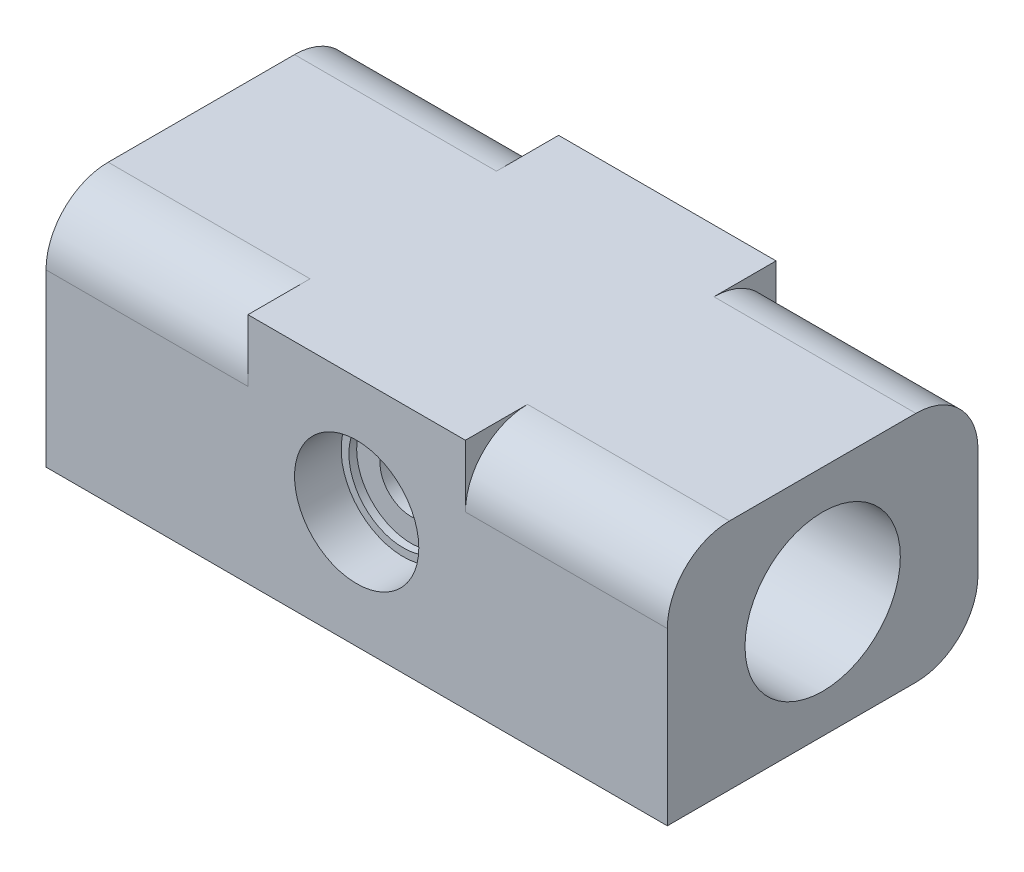
SolidWorks part; units mm, degrees
material "ABS"
ref_plane "前基準面" through (0, 0, 0) normal (0, 0, 1) x (1, 0, 0)
ref_plane "上基準面" through (0, 0, 0) normal (0, 1, 0) x (1, 0, 0)
ref_plane "右基準面" through (0, 0, 0) normal (1, 0, 0) x (0, 0, -1)
sketch "草圖1" plane through (0, 0, 0) normal (1, 0, 0) x (0, 0, -1)
  line L1 (-10, 7.5) -> (10, 7.5)
  line L2 (-10, 7.5) -> (-10, -7.5)
  line L3 (-10, -7.5) -> (10, -7.5)
  line L4 (10, 7.5) -> (10, -7.5)
  line L5 (-10, 7.5) -> (10, -7.5) construction
  line L6 (-10, -7.5) -> (10, 7.5) construction
  circle A0 centre (0, 0) radius 5
  point P0 (0, 0)
  dimension "D1" = 10
  dimension "D2" = 20
  dimension "D3" = 15
extrude "填料-伸長1" add sketch "草圖1" along normal blind 40
sketch "草圖2" plane through (0, 0, 10) normal (0, 0, 1) x (1, 0, 0)
  line L0 (0, 0) -> (40, 0) construction
  line L1 (0, 7.5) -> (0, -7.5) construction
  line L2 (40, 7.5) -> (40, -7.5) construction
  circle A1 centre (20, 0) radius 4
  dimension "D2" = 8
extrude "除料-伸長1" cut sketch "草圖2" against normal blind 3
mirror "鏡射1" about plane through (0, 0, 0) normal (0, 0, 1) of "除料-伸長1"
sketch "草圖3" plane through (0, 0, 7) normal (0, 0, 1) x (1, 0, 0)
  circle A0 centre (20, 0) radius 2
  dimension "D1" = 4
extrude "除料-伸長2" cut sketch "草圖3" against normal through all
sketch "草圖4" plane through (0, 0, 0) normal (-1, 0, 0) x (0, 0, 1)
  line L1 (-6, 7.5) -> (6, 7.5)
  line L2 (-10, 3.5) -> (-10, -3.5)
  line L3 (-6, -7.5) -> (10, -7.5)
  line L4 (10, 3.5) -> (10, -7.5)
  line L5 (-10, 7.5) -> (10, -7.5) construction
  line L6 (-10, -7.5) -> (10, 7.5) construction
  line L7 (-13.2969, 9.2023) -> (13.2969, 9.2023)
  line L8 (-13.2969, 9.2023) -> (-13.2969, -9.2023)
  line L9 (-13.2969, -9.2023) -> (13.2969, -9.2023)
  line L10 (13.2969, 9.2023) -> (13.2969, -9.2023)
  line L11 (-13.2969, 9.2023) -> (13.2969, -9.2023) construction
  line L12 (-13.2969, -9.2023) -> (13.2969, 9.2023) construction
  arc A0 (-6, 7.5) -> (-10, 3.5) centre (-6, 3.5) ccw
  arc A1 (-10, -3.5) -> (-6, -7.5) centre (-6, -3.5) ccw
  arc A3 (6, 7.5) -> (10, 3.5) centre (6, 3.5) cw
  point P0 (0, 0)
  point P7 (0, 0)
  dimension "D1" = 4
extrude "除料-伸長3" cut sketch "草圖4" against normal blind 13
ref_plane "平面1" through (20, 0, 0) normal (1, 0, 0) x (0, 0, -1)
mirror "鏡射2" about plane through (20, 0, 0) normal (1, 0, 0) of "除料-伸長3"
sketch "草圖5" plane through (0, 0, -7) normal (0, 0, -1) x (-1, 0, 0)
  circle A0 centre (-20, 0) radius 3.5
  dimension "D1" = 7
extrude "除料-伸長4" cut sketch "草圖5" against normal blind 0.5
mirror "鏡射3" about plane through (0, 0, 0) normal (0, 0, 1) of "除料-伸長4"
sketch "草圖6" plane through (0, 0, -10) normal (0, 0, 1) x (1, 0, 0)
  line L0 (17.25, -4.7631) -> (15.6699, -7.5) construction
  line L2 (15.6699, -7.5) -> (24.3301, -7.5)
  line L4 (24.3301, -7.5) -> (22.75, -4.7631) construction
  line L5 (20, -8.25) -> (20, 8.25) construction
  line L6 (22.75, -4.7631) -> (27.7296, -1.8881)
  line L7 (12.2704, -1.8881) -> (9.5818, -2.5449)
  line L8 (33.2791, -7.5) -> (24.3301, -7.5)
  line L9 (17.25, -4.7631) -> (12.2704, -1.8881)
  line L10 (9.5818, -2.5449) -> (6.7209, -7.5)
  line L12 (6.7209, -7.5) -> (15.6699, -7.5)
  line L13 (27.7296, -1.8881) -> (30.4182, -2.5449)
  line L14 (30.4182, -2.5449) -> (33.2791, -7.5)
  line L16 (27, -7.5) -> (40, -7.5) construction
  line L17 (13, -7.5) -> (0, -7.5) construction
  arc A0 (22.75, -4.7631) -> (17.25, -4.7631) centre (20, 0) cw
  point P10 (20, -7.5)
  dimension "D1" = 5.5
  dimension "D2" = 60
  dimension "D3" = 5.75
  dimension "D4" = 2
extrude "除料-伸長5" cut sketch "草圖6" along normal blind 6
sketch "草圖7" plane through (0, -7.5, 0) normal (0, -1, 0) x (1, 0, 0)
  line L0 (20, 10) -> (20, -4)
  line L1 (40, 10) -> (0, 10) construction
  line L2 (6.7209, -4) -> (33.2791, -4) construction
  point P6 (20, 9)
  dimension "D1" = 1
